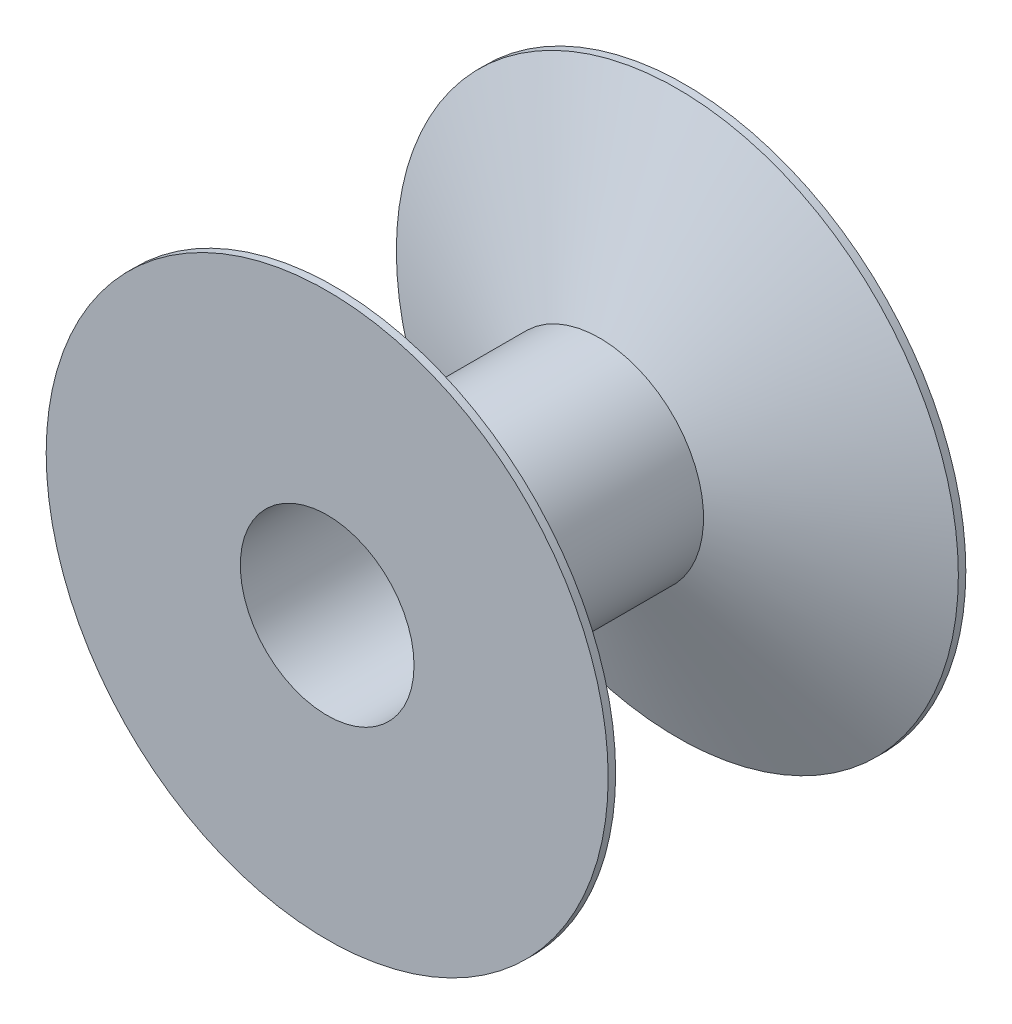
SolidWorks part; units mm, degrees
ref_plane "정면" through (0, 0, 0) normal (0, 0, 1) x (1, 0, 0)
ref_plane "윗면" through (0, 0, 0) normal (0, 1, 0) x (1, 0, 0)
ref_plane "우측면" through (0, 0, 0) normal (1, 0, 0) x (0, 0, -1)
sketch "스케치1" plane through (0, 0, 0) normal (0, 0, 1) x (1, 0, 0)
  circle A0 centre (0, 0) radius 5.1
  circle A1 centre (0, 0) radius 6.1
  dimension "D1" = 10.2
  dimension "D2" = 12.2
extrude "보스-돌출1" add sketch "스케치1" along normal blind 11 contours A0
ref_plane "평면1" through (0, 0, 5.5) normal (0, 0, 1) x (1, 0, 0)
sketch "스케치2" plane through (0, 0, 11) normal (0, 0, 1) x (1, 0, 0)
  circle A0 centre (0, 0) radius 5.1
  circle A1 centre (0, 0) radius 17.5
  dimension "D1" = 35
  dimension "D2" = 10.2
extrude "보스-돌출2" add sketch "스케치2" along normal blind 5
mirror "대칭 복사1" about plane through (0, 0, 5.5) normal (0, 0, 1) of "보스-돌출2"
sketch "스케치3" plane through (0, 0, 0) normal (0, 1, 0) x (1, 0, 0)
  line L0 (-17.5, 5) -> (-6.1, 0)
  line L1 (-6.1, 0) -> (-17.5, 0)
  line L2 (-17.5, 0) -> (-17.5, 5)
  line L3 (0, 9.434) -> (0, -28.6216) construction
  line L4 (-55, -5.5) -> (55, -5.5) construction
  line L5 (-17.5, -11) -> (-17.5, -16)
  line L6 (-6.1, -11) -> (-17.5, -11)
  line L7 (-17.5, -16) -> (-6.1, -11)
revolve "컷-회전1" cut sketch "스케치3" angle 360 about L3
sketch "스케치4" plane through (0, 0, 16) normal (0, 0, 1) x (1, 0, 0)
  circle A0 centre (0, 0) radius 16.5
  dimension "D1" = 33
extrude "컷-돌출1" cut sketch "스케치4" against normal through all flip side to cut
